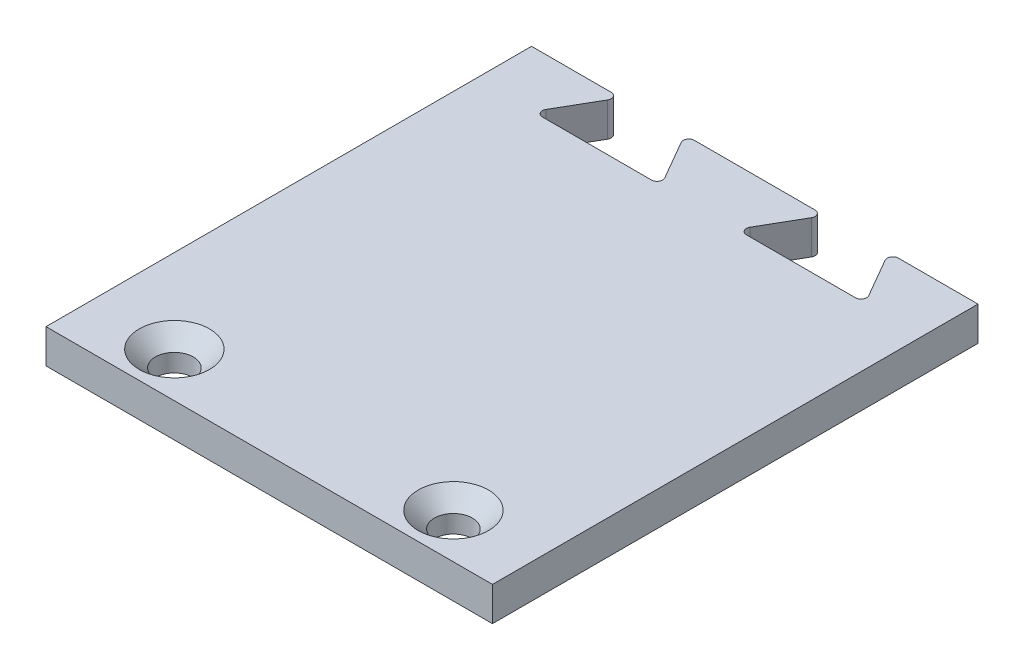
SolidWorks part; units mm, degrees
ref_plane "Front Plane" through (0, 0, 0) normal (0, 0, 1) x (1, 0, 0)
ref_plane "Top Plane" through (0, 0, 0) normal (0, 1, 0) x (1, 0, 0)
ref_plane "Right Plane" through (0, 0, 0) normal (1, 0, 0) x (0, 0, -1)
sketch "Sketch1" plane through (0, 0, 0) normal (0, 1, 0) x (1, 0, 0)
  line L0 (0, 0) -> (0, 43.5)
  line L1 (0, 43.5) -> (8, 43.5)
  line L2 (8, 43.5) -> (5.1132, 38.5)
  line L3 (5.1132, 38.5) -> (16.6132, 38.5)
  line L4 (16.6132, 38.5) -> (13.7265, 43.5)
  line L5 (13.7265, 43.5) -> (26.2735, 43.5)
  line L6 (26.2735, 43.5) -> (23.3868, 38.5)
  line L7 (23.3868, 38.5) -> (34.8868, 38.5)
  line L8 (34.8868, 38.5) -> (32, 43.5)
  line L9 (32, 43.5) -> (40, 43.5)
  line L10 (40, 43.5) -> (40, 0)
  line L11 (40, 0) -> (0, 0)
  dimension "D1" = 43.5
  dimension "D2" = 40
  dimension "D3" = 8
  dimension "D4" = 11.5
  dimension "D5" = 11.5
  dimension "D6" = 8
  dimension "D7" = 5
  dimension "D8" = 5
  dimension "D9" = 5
  dimension "D10" = 5
  dimension "D11" = 60
  dimension "D12" = 60
  dimension "D13" = 60
extrude "Boss-Extrude1" add sketch "Sketch1" along normal blind 3.05
fillet "Fillet3" radius 0.5 8 edges at (34.8868, 1.525, -38.5) (32, 1.525, -43.5) (23.3868, 1.525, -38.5) (26.2735, 1.525, -43.5) (13.7265, 1.525, -43.5) (16.6132, 1.525, -38.5) (5.1132, 1.525, -38.5) (8, 1.525, -43.5)
hole_wizard "CSK for M3 Flat Head Machine Screw1" positions "Sketch6" profile "Sketch7" countersink size "M3" standard "ANSI Metric" end condition through all
sketch "Sketch6" plane through (0, 3.05, 0) normal (0, 1, 0) x (1, 0, 0)
  line L0 (0, 43.5) -> (0, 0) construction
  line L1 (40, 0) -> (40, 43.5) construction
  line L2 (0, 4) -> (40, 4) construction
  line L4 (0, 0) -> (40, 0) construction
  point P0 (7.5, 4)
  point P2 (32.5, 4)
  point P14 (0, 0)
  dimension "D1" = 7.5
  dimension "D2" = 7.5
  dimension "D3" = 4
sketch "Sketch7" plane through (7.5, 3.05, -4) normal (1, 0, 0) x (0, 0, 1)
  line L0 (0, 0) -> (0, 3.05)
  line L1 (0, 3.05) -> (1.7, 3.05)
  line L2 (1.7, 3.05) -> (1.7, 1.45)
  line L3 (1.7, 1.45) -> (3.15, 0)
  line L5 (3.15, 0) -> (0, 0)
  line L6 (-1.7, 1.45) -> (-3.15, 0) construction
  line L11 (0, -6.35) -> (0, 107.95) construction
  dimension "Thru Hole Dia." = 3.4
  dimension "Thru Hole Depth" = 3.05
  dimension "Near C'Sink Dia." = 6.3
  dimension "Near C'Sink Angle" = 90
